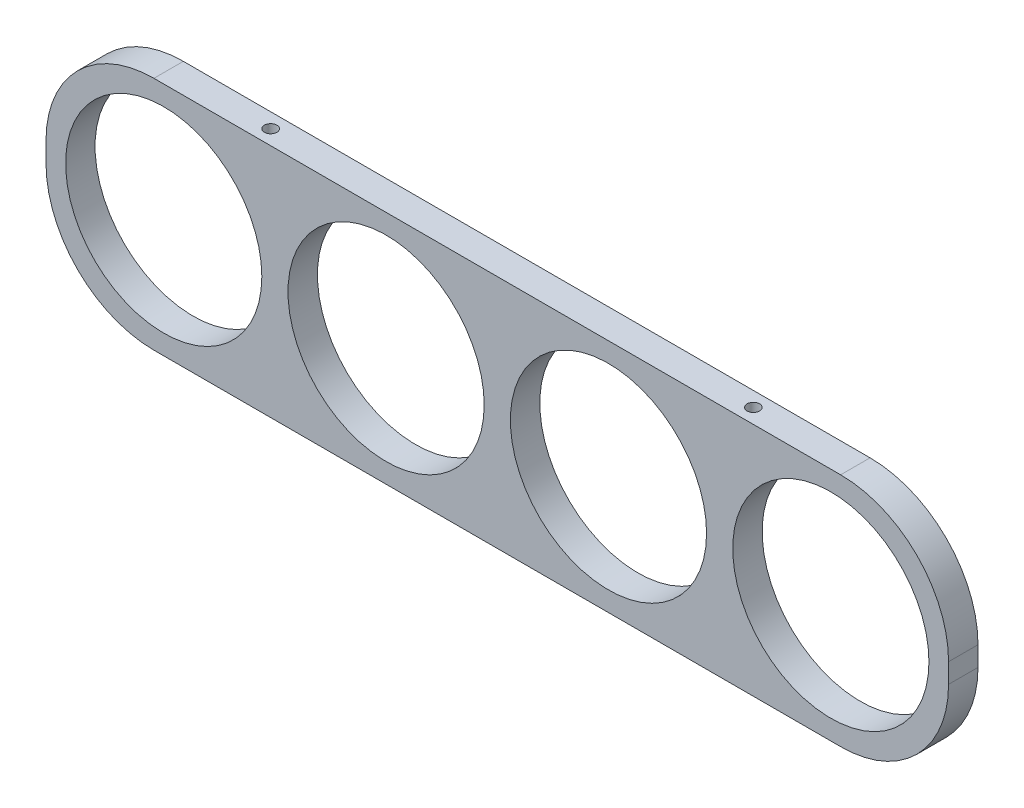
SolidWorks part; units mm, degrees
material "Delrin 2700 NC010, Low Viscosity Acetal Copolymer (SS)"
ref_plane "Front Plane" through (0, 0, 0) normal (0, 0, 1) x (1, 0, 0)
ref_plane "Top Plane" through (0, 0, 0) normal (0, 1, 0) x (1, 0, 0)
ref_plane "Right Plane" through (0, 0, 0) normal (1, 0, 0) x (0, 0, -1)
sketch "Sketch1" plane through (0, 0, 0) normal (0, 0, 1) x (1, 0, 0)
  line L1 (146.05, 38.1) -> (-146.05, 38.1)
  line L2 (146.05, 38.1) -> (146.05, -38.1)
  line L3 (146.05, -38.1) -> (-146.05, -38.1)
  line L4 (-146.05, 38.1) -> (-146.05, -38.1)
  line L5 (146.05, 38.1) -> (-146.05, -38.1) construction
  line L6 (146.05, -38.1) -> (-146.05, 38.1) construction
  point P0 (0, 0)
  dimension "D1" = 292.1
  dimension "D2" = 76.2
extrude "Boss-Extrude1" add sketch "Sketch1" along normal mid plane 9.525
sketch "Sketch2" plane through (0, 0, 4.7625) normal (0, 0, 1) x (1, 0, 0)
  line L0 (-107.95, 0) -> (-35.9833, 0) construction
  line L1 (-35.9833, 0) -> (35.9833, 0) construction
  line L2 (35.9833, 0) -> (107.95, 0) construction
  line L4 (-146.05, 38.1) -> (-146.05, -38.1) construction
  circle A0 centre (-107.95, 0) radius 31.75
  circle A1 centre (-35.9833, 0) radius 31.75
  circle A2 centre (35.9833, 0) radius 31.75
  circle A3 centre (107.95, 0) radius 31.75
  dimension "D1" = 63.5
  dimension "D2" = 38.1
extrude "Cut-Extrude1" cut sketch "Sketch2" against normal through all
fillet "Fillet1" radius 34.925 4 edges at (-146.05, 38.1, 0) (146.05, -38.1, 0) (-146.05, -38.1, 0) (146.05, 38.1, 0)
hole_wizard "#10-32 Tapped Hole2" positions "Sketch6" profile "Sketch7" tap size "#10-32" standard "ANSI Inch"
sketch "Sketch6" plane through (0, 38.1, 0) normal (0, 1, 0) x (1, 0, 0)
  line L0 (-78.105, 0) -> (78.105, 0) construction
  point P0 (-78.105, 0)
  point P2 (78.105, 0)
  dimension "D1" = 156.21
sketch "Sketch7" plane through (-78.105, 38.1, 0) normal (1, 0, 0) x (0, 0, 1)
  line L0 (0, 0) -> (0, 20.2633)
  line L1 (0, 20.2633) -> (2.0193, 19.05)
  line L2 (2.0193, 19.05) -> (2.0193, 0)
  line L5 (2.0193, 0) -> (0, 0)
  line L10 (0, 20.2633) -> (-2.0193, 19.05) construction
  line L11 (0, -6.35) -> (0, 107.95) construction
  dimension "Tap Drill Dia." = 4.0386
  dimension "Tap Drill Depth" = 19.05
  dimension "Drill Angle" = 118
cosmetic thread "Hole Thread5" parameters "D1"=9.652, "D2"=4.826
cosmetic thread "Hole Thread6" parameters "D1"=9.652, "D2"=4.826
